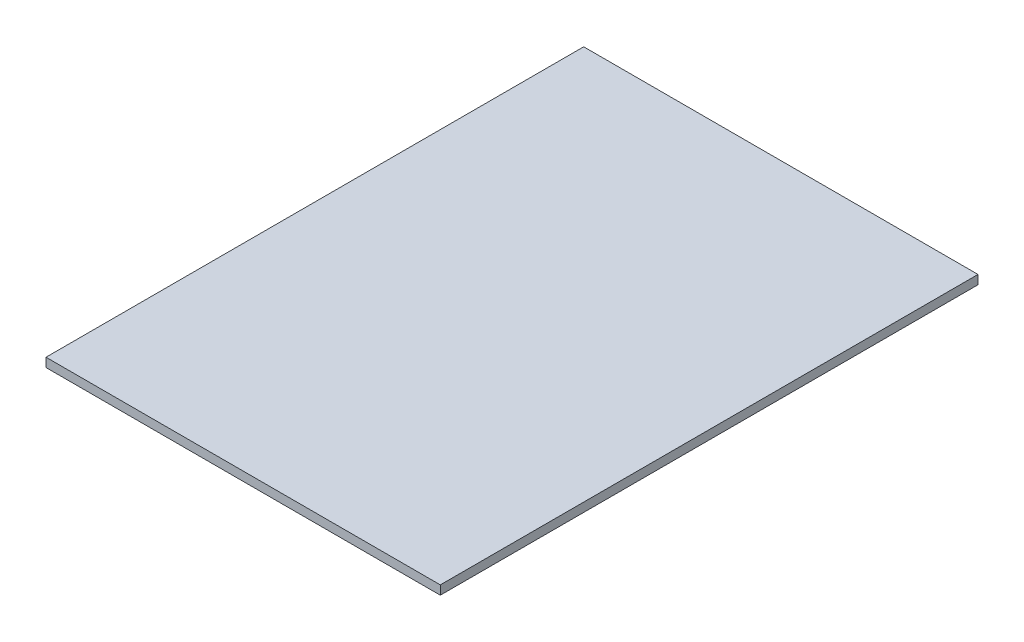
SolidWorks part; units mm, degrees
ref_plane "Plan de face" through (0, 0, 0) normal (0, 0, 1) x (1, 0, 0)
ref_plane "Plan de dessus" through (0, 0, 0) normal (0, 1, 0) x (1, 0, 0)
ref_plane "Plan de droite" through (0, 0, 0) normal (1, 0, 0) x (0, 0, -1)
sketch "Esquisse1" plane through (0, 0, 0) normal (0, 1, 0) x (1, 0, 0)
  line L1 (-110, -150) -> (110, -150)
  line L2 (-110, -150) -> (-110, 150)
  line L3 (-110, 150) -> (110, 150)
  line L4 (110, -150) -> (110, 150)
  line L5 (-110, -150) -> (110, 150) construction
  line L6 (-110, 150) -> (110, -150) construction
  point P0 (0, 0)
extrude "Boss.-Extru.1" add sketch "Esquisse1" along normal blind 5 contours L3 L4 L1 L2
